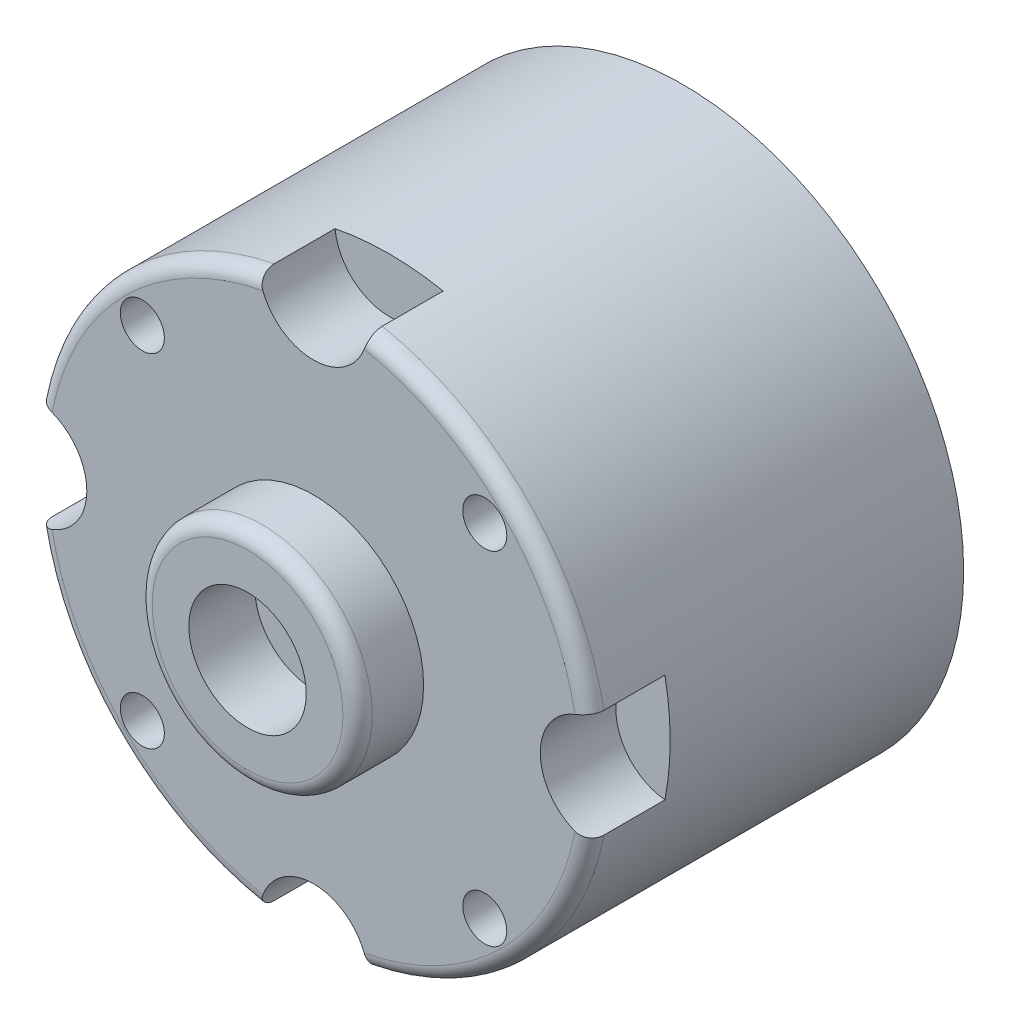
SolidWorks part; units mm, degrees
ref_plane "Front Plane" through (0, 0, 0) normal (0, 0, 1) x (1, 0, 0)
ref_plane "Top Plane" through (0, 0, 0) normal (0, 1, 0) x (1, 0, 0)
ref_plane "Right Plane" through (0, 0, 0) normal (1, 0, 0) x (0, 0, -1)
sketch "Sketch2" plane through (0, 0, 0) normal (0, 0, 1) x (1, 0, 0)
  circle A0 centre (0, 0) radius 19.15
  dimension "D1" = 38.3
extrude "Boss-Extrude1" add sketch "Sketch2" along normal blind 25.15
sketch "Sketch3" plane through (0, 0, 25.15) normal (0, 0, 1) x (1, 0, 0)
  line L0 (0, 20.842) -> (0, -22.1866) construction
  line L1 (-21.0758, 0) -> (22.7128, 0) construction
  line L2 (0, 0) -> (13.5411, 13.5411) construction
  line L3 (0, 0) -> (-13.5411, -13.5411) construction
  circle A0 centre (0, 0) radius 19.15 construction
  circle A1 centre (11.6673, 11.6673) radius 1.5
  circle A2 centre (-11.6673, -11.6673) radius 1.5
  circle A3 centre (11.6673, -11.6673) radius 1.5
  circle A4 centre (-11.6673, 11.6673) radius 1.5
  circle A5 centre (0, 19.15) radius 3.7
  circle A6 centre (0, -19.15) radius 3.7
  circle A7 centre (-19.15, 0) radius 3.7
  circle A8 centre (19.15, 0) radius 3.7
  dimension "D1" = 3
  dimension "D2" = 3
  dimension "D3" = 16.5
  dimension "D4" = 7.4
  dimension "D5" = 7.4
  dimension "D6" = 16.5
extrude "Cut-Extrude1" cut sketch "Sketch3" against normal blind 5.15
sketch "Sketch4" plane through (0, 0, 25.15) normal (0, 0, 1) x (1, 0, 0)
  circle A0 centre (0, 0) radius 7.5
  dimension "D1" = 15
extrude "Boss-Extrude2" add sketch "Sketch4" along normal blind 4.5
sketch "Sketch5" plane through (0, 0, 29.65) normal (0, 0, 1) x (1, 0, 0)
  circle A0 centre (0, 0) radius 4
  dimension "D1" = 8
extrude "Cut-Extrude2" cut sketch "Sketch5" against normal blind 4.5
fillet "Fillet1" radius 1 5 edges at (13.5411, -13.5411, 25.15) (13.5411, 13.5411, 25.15) (-13.5411, -13.5411, 25.15) (-13.5411, 13.5411, 25.15) (7.5, 0, 29.65)
